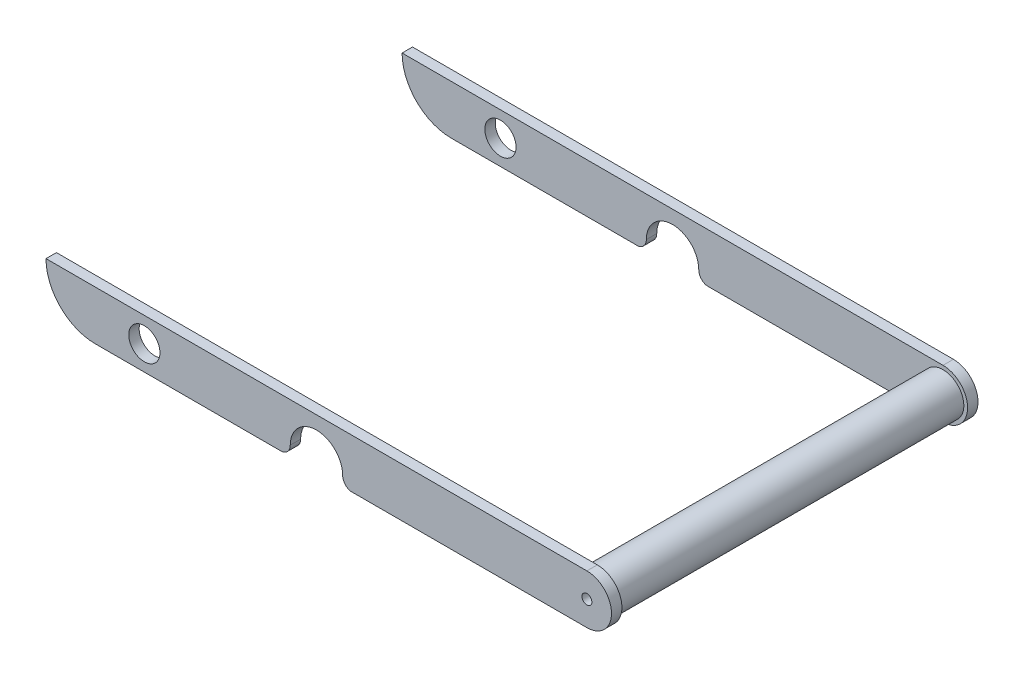
SolidWorks part; units mm, degrees
ref_plane "Front Plane" through (0, 0, 0) normal (0, 0, 1) x (1, 0, 0)
ref_plane "Top Plane" through (0, 0, 0) normal (0, 1, 0) x (1, 0, 0)
ref_plane "Right Plane" through (0, 0, 0) normal (1, 0, 0) x (0, 0, -1)
sketch "Sketch1" plane through (0, 0, 0) normal (0, 0, 1) x (1, 0, 0)
  line L1 (0, 0) -> (150, 0)
  line L3 (-15, 15) -> (150, 15)
  arc A1 (150, 0) -> (150, 15) centre (150, 7.5) ccw
  circle A2 centre (15, 7.5) radius 4.7625
  arc A3 (0, 0) -> (-15, 15) centre (0, 15) cw
  dimension "D4" = 15
  dimension "D6" = 9.525
  dimension "D3" = 15
  dimension "D1" = 30
  dimension "D2" = 135
  dimension "D5" = 7.5
extrude "Boss-Extrude1" add sketch "Sketch1" along normal blind 3.175
sketch "Sketch2" plane through (0, 0, 3.175) normal (0, 0, 1) x (1, 0, 0)
  circle A0 centre (150, 7.5) radius 6.35
  dimension "D1" = 12.7
extrude "Boss-Extrude2" add sketch "Sketch2" along normal blind 105.4492
sketch "Sketch3" plane through (0, 0, 108.6242) normal (0, 0, 1) x (1, 0, 0)
  line L0 (0, 0) -> (150, 0)
  line L1 (-15, 15) -> (150, 15)
  line L2 (150, 15) -> (-15, 15) construction
  arc A1 (150, 0) -> (150, 15) centre (150, 7.5) ccw
  circle A2 centre (15, 7.5) radius 4.7625
  arc A3 (0, 0) -> (-15, 15) centre (0, 15) cw
  dimension "D4" = 15
  dimension "D6" = 9.525
  dimension "D3" = 15
  dimension "D1" = 30
  dimension "D2" = 135
  dimension "D5" = 7.5
extrude "Boss-Extrude3" add sketch "Sketch3" along normal blind 3.175
sketch "Sketch5" plane through (0, 0, 111.7992) normal (0, 0, 1) x (1, 0, 0)
  line L0 (0, 0) -> (150, 0) construction
  line L1 (57.0175, 0) -> (77.9825, 0)
  circle A0 centre (150, 7.5) radius 1.5184
  arc A1 (150, 0) -> (150, 15) centre (150, 7.5) ccw construction
  arc A2 (75.5, 2.955) -> (59.5, 2.955) centre (67.5, 2.955) ccw
  arc A3 (59.5, 2.955) -> (57.0175, 0) centre (56.5, 2.955) cw
  arc A4 (75.5, 2.955) -> (77.9825, 0) centre (78.5, 2.955) ccw
  point P7 (59.5, 2.955)
  point P8 (75.5, 2.955)
  dimension "D1" = 8
  dimension "D2" = 3
  dimension "D3" = 82.5
extrude "Cut-Extrude1" cut sketch "Sketch5" against normal through all
equation "\"D4@Sketch1\"=\"D3@Sketch1\""
equation "\"D5@Sketch1\"=\"D3@Sketch1\"/2"
equation "\"D4@Sketch3\"=\"D3@Sketch3\""
equation "\"D5@Sketch3\"=\"D3@Sketch3\"/2"
equation "\"D2@Sketch3\"= \"D2@Sketch1\""
equation "\"D3@Sketch5\"= \"D2@Sketch1\" - 52.5"
